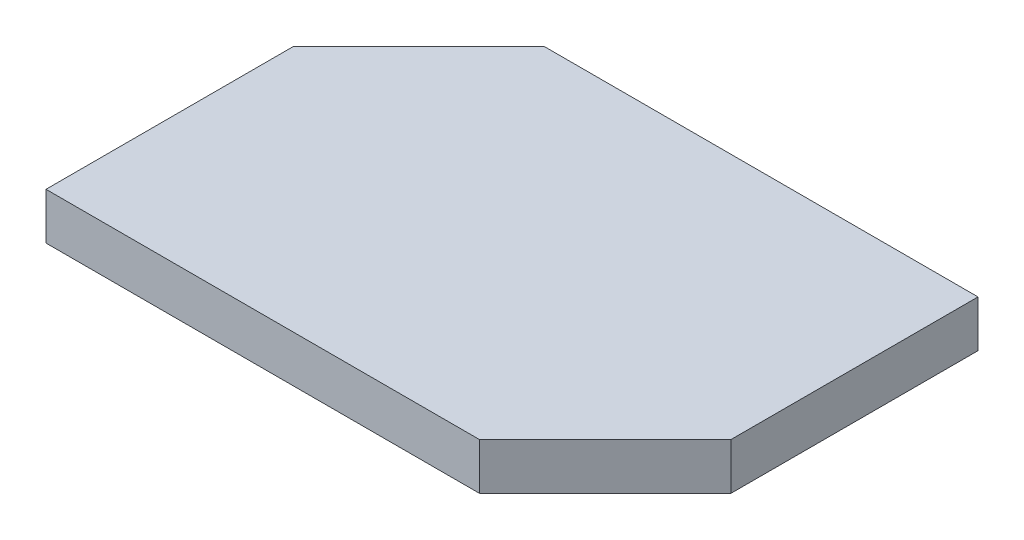
SolidWorks part; units mm, degrees
ref_plane "Plano frontal" through (0, 0, 0) normal (0, 0, 1) x (1, 0, 0)
ref_plane "Plano superior" through (0, 0, 0) normal (0, 1, 0) x (1, 0, 0)
ref_plane "Plano direito" through (0, 0, 0) normal (1, 0, 0) x (0, 0, -1)
sketch "Esboço1" plane through (0, 0, 0) normal (0, 1, 0) x (1, 0, 0)
  line L0 (0.6, 0.4) -> (-0.6, -0.4) construction
  line L1 (-0.6, 0.4) -> (0.6, 0.4)
  line L2 (-0.6, 0.4) -> (-0.6, -0.4)
  line L3 (-0.6, -0.4) -> (0.6, -0.4)
  line L4 (0.6, 0.4) -> (0.6, -0.4)
  dimension "D1" = 1.2
  dimension "D2" = 0.8
extrude "Extrusão1" add sketch "Esboço1" along normal blind 0.1
chamfer "Chanfro1" distance 0.27 angle 45 1 edges at (0.6, 0.05, 0.4)
chamfer "Chanfro2" distance 0.27 angle 45 1 edges at (-0.6, 0.05, -0.4)
